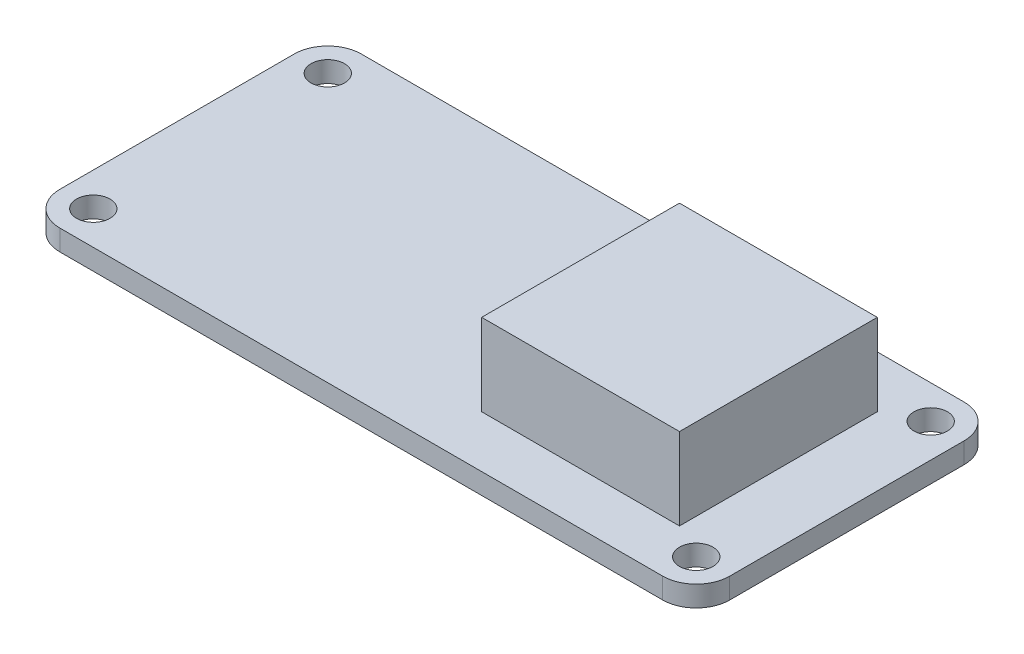
SolidWorks part; units mm, degrees
ref_plane "Front Plane" through (0, 0, 0) normal (0, 0, 1) x (1, 0, 0)
ref_plane "Top Plane" through (0, 0, 0) normal (0, 1, 0) x (1, 0, 0)
ref_plane "Right Plane" through (0, 0, 0) normal (1, 0, 0) x (0, 0, -1)
sketch "Sketch1" plane through (0, 0, 0) normal (0, 1, 0) x (1, 0, 0)
  line L1 (-25.4, -11.43) -> (25.4, -11.43)
  line L2 (-25.4, -11.43) -> (-25.4, 11.43)
  line L3 (-25.4, 11.43) -> (25.4, 11.43)
  line L4 (25.4, -11.43) -> (25.4, 11.43)
  line L5 (-25.4, -11.43) -> (25.4, 11.43) construction
  line L6 (-25.4, 11.43) -> (25.4, -11.43) construction
  point P0 (0, 0)
  dimension "D1" = 22.86
  dimension "D2" = 50.8
extrude "Boss-Extrude1" add sketch "Sketch1" along normal blind 1.57
sketch "Sketch2" plane through (0, 1.57, 0) normal (0, 1, 0) x (1, 0, 0)
  line L0 (25.4, 11.43) -> (-25.4, 11.43) construction
  line L1 (-22.86, -8.89) -> (22.86, -8.89) construction
  line L2 (-22.86, -8.89) -> (-22.86, 8.89) construction
  line L3 (-22.86, 8.89) -> (22.86, 8.89) construction
  line L4 (22.86, -8.89) -> (22.86, 8.89) construction
  line L5 (-22.86, -8.89) -> (22.86, 8.89) construction
  line L6 (-22.86, 8.89) -> (22.86, -8.89) construction
  line L8 (0, -11.43) -> (0, 11.43) construction
  line L9 (-25.4, 0) -> (25.4, 0) construction
  line L10 (25.4, -11.43) -> (25.4, 11.43) construction
  line L11 (-25.4, 11.43) -> (-25.4, -11.43) construction
  line L12 (5.2, -7.5) -> (20.2, -7.5)
  line L13 (5.2, -7.5) -> (5.2, 7.5)
  line L14 (5.2, 7.5) -> (20.2, 7.5)
  line L15 (20.2, -7.5) -> (20.2, 7.5)
  line L16 (5.2, -7.5) -> (20.2, 7.5) construction
  line L17 (5.2, 7.5) -> (20.2, -7.5) construction
  point P0 (0, 0)
  point P6 (12.7, 0)
  point P15 (0, 0)
  point P20 (0, 0)
  dimension "D1" = 45.72
  dimension "D2" = 17.78
  dimension "D3" = 38.1
  dimension "D4" = 15
  dimension "D5" = 15
hole_wizard "1/16 (0.1) Dowel Hole1" positions "3DSketch1" profile "Sketch3" hole size "1/16" standard "ANSI Inch" end condition through all
sketch3d "3DSketch1"
  point P0 (-22.86, 1.57, -8.89)
  point P3 (22.86, 1.57, -8.89)
  point P6 (22.86, 1.57, 8.89)
  point P9 (-22.86, 1.57, 8.89)
sketch "Sketch3" plane through (-22.86, 1.57, -8.89) normal (1, 0, 0) x (0, 0, 1)
  line L0 (0, 0) -> (0, 1.57)
  line L1 (0, 1.57) -> (1.27, 1.57)
  line L2 (1.27, 1.57) -> (1.27, 0)
  line L5 (1.27, 0) -> (0, 0)
  line L11 (0, -6.35) -> (0, 107.95) construction
  dimension "Thru Hole Dia." = 2.54
  dimension "Thru Hole Depth" = 1.57
fillet "Fillet1" radius 2.54 4 edges at (25.4, 0.785, -11.43) (25.4, 0.785, 11.43) (-25.4, 0.785, 11.43) (-25.4, 0.785, -11.43)
extrude "Boss-Extrude2" add sketch "Sketch2" along normal blind 6.2
sketch "Sketch5" plane through (0, 0, 0) normal (0, -1, 0) x (1, 0, 0)
  line L0 (0, 11.43) -> (0, -11.43) construction
  line L1 (-22.86, 11.43) -> (22.86, 11.43) construction
  line L2 (22.86, -11.43) -> (-22.86, -11.43) construction
  line L3 (-22.86, 8.89) -> (22.86, 8.89) construction
